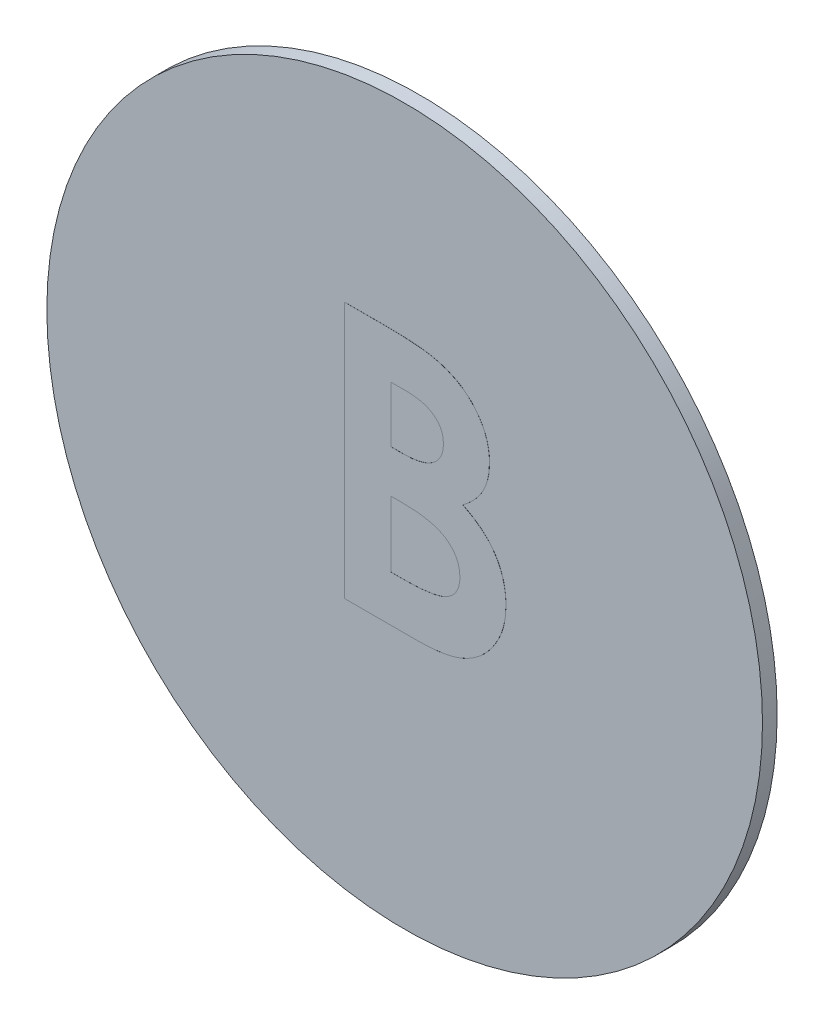
SolidWorks part; units mm, degrees
ref_plane "Front Plane" through (0, 0, 0) normal (0, 0, 1) x (1, 0, 0)
ref_plane "Top Plane" through (0, 0, 0) normal (0, 1, 0) x (1, 0, 0)
ref_plane "Right Plane" through (0, 0, 0) normal (1, 0, 0) x (0, 0, -1)
sketch "Sketch1" plane through (0, 0, 0) normal (0, 0, 1) x (1, 0, 0)
  circle A0 centre (-24.02, -6.7749) radius 4.88
extrude "Boss-Extrude1" add sketch "Sketch1" along normal blind 0.2
sketch "Sketch3" plane through (0, 0, 0.2) normal (0, 0, 1) x (1, 0, 0)
  text T0 "<b>B</b>"
extrude "Boss-Extrude2" add sketch "Sketch3" along normal blind 0.001
